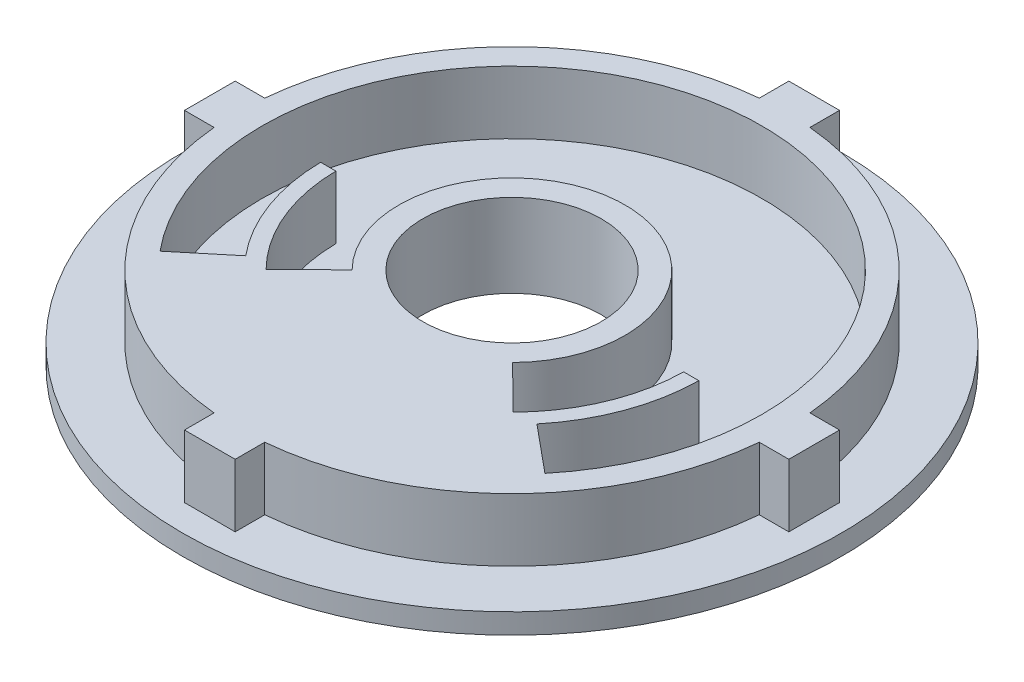
SolidWorks part; units mm, degrees
ref_plane "Front Plane" through (0, 0, 0) normal (0, 0, 1) x (1, 0, 0)
ref_plane "Top Plane" through (0, 0, 0) normal (0, 1, 0) x (1, 0, 0)
ref_plane "Right Plane" through (0, 0, 0) normal (1, 0, 0) x (0, 0, -1)
sketch "Sketch1" plane through (0, 0, 0) normal (0, 1, 0) x (1, 0, 0)
  line L0 (-17.5, -17.3601) -> (-13.2404, -13.1345)
  line L1 (0, -55) -> (0, 55) construction
  line L2 (17.5, -17.3601) -> (13.2404, -13.1345)
  line L3 (-18.6487, -0.2213) -> (-17.1486, -0.2214)
  line L4 (-17.5, -17.3601) -> (3.5272, -38.5567) construction
  line L5 (18.6487, -0.2213) -> (17.1486, -0.2214)
  line L6 (-12.1755, -12.0781) -> (-7.9158, -7.8525)
  line L7 (12.1755, -12.0781) -> (7.9158, -7.8525)
  circle A0 centre (0, 0) radius 27
  arc A1 (7.9158, -7.8525) -> (-7.9158, -7.8525) centre (0, 0) ccw
  arc A2 (17.5, -17.3601) -> (-17.5, -17.3601) centre (0, 0) ccw
  circle A3 centre (0, 0) radius 8.8
  arc A4 (14.1575, 11.0034) -> (12.7079, -12.6063) centre (-0.0251, 0.0249) cw construction
  circle A5 centre (0, 0) radius 17.9 construction
  arc A6 (-13.2404, -13.1345) -> (-18.6487, -0.2213) centre (0, 0) cw
  arc A7 (-12.1755, -12.0781) -> (-17.1486, -0.2214) centre (0, 0) cw
  arc A8 (13.2404, -13.1345) -> (18.6487, -0.2213) centre (0, 0) ccw
  arc A9 (12.1755, -12.0781) -> (17.1486, -0.2214) centre (0, 0) ccw
  dimension "D1" = 54
  dimension "D2" = 2.35
  dimension "D3" = 13.5
  dimension "D4" = 2.35
  dimension "D6" = 1.5
  dimension "D7" = 0.75
  dimension "D8" = 14
  dimension "D5" = 35
extrude "Boss-Extrude1" add sketch "Sketch1" along normal blind 6.2
sketch "Sketch2" plane through (0, 0, 0) normal (0, -1, 0) x (1, 0, 0)
  circle A0 centre (0, 0) radius 32.5
  circle A1 centre (0, 0) radius 8.8
  circle A2 centre (0, 0) radius 8.8 construction
  dimension "D1" = 65
extrude "Boss-Extrude2" add sketch "Sketch2" along normal blind 2
sketch "Sketch3" plane through (0, 0, 0) normal (0, 1, 0) x (1, 0, 0)
  line L0 (0, -55) -> (0, 55) construction
  line L1 (-2.5, 29.8) -> (2.5, 29.8)
  line L2 (-2.5, 29.8) -> (-2.5, 25.4032)
  line L3 (-2.5, 25.4032) -> (2.5, 25.4032)
  line L4 (2.5, 29.8) -> (2.5, 25.4032)
  line L5 (-2.5, 29.8) -> (2.5, 25.4032) construction
  line L6 (-2.5, 25.4032) -> (2.5, 29.8) construction
  line L7 (29.8, 2.5) -> (25.4032, 2.5)
  line L8 (29.8, 2.5) -> (29.8, -2.5)
  line L9 (29.8, -2.5) -> (25.4032, -2.5)
  line L10 (25.4032, 2.5) -> (25.4032, -2.5)
  line L11 (2.5, -29.8) -> (2.5, -25.4032)
  line L12 (2.5, -29.8) -> (-2.5, -29.8)
  line L13 (-2.5, -29.8) -> (-2.5, -25.4032)
  line L14 (2.5, -25.4032) -> (-2.5, -25.4032)
  line L15 (-29.8, -2.5) -> (-25.4032, -2.5)
  line L16 (-29.8, -2.5) -> (-29.8, 2.5)
  line L17 (-29.8, 2.5) -> (-25.4032, 2.5)
  line L18 (-25.4032, -2.5) -> (-25.4032, 2.5)
  circle A1 centre (0, 0) radius 27 construction
  point P0 (0, 27.6016)
  dimension "D2" = 29.8
  dimension "D1" = 5
  dimension "D3" = 4
extrude "Boss-Extrude3" add sketch "Sketch3" along normal up to surface (6.2 mm away) up to face at (0, 6.2, 3.562)
sketch "Sketch5" plane through (0, 0, 0) normal (0, 1, 0) x (1, 0, 0)
  line L0 (-18.9776, -15.7313) -> (-13.2035, -10.9449)
  line L2 (-12.1755, -12.0781) -> (-17.7339, -18.2046)
  line L3 (-17.7339, -18.2046) -> (-18.9776, -15.7313)
  line L8 (-18.9776, -15.7313) -> (-26.2675, -6.937) construction
  arc A0 (17.5, -17.3601) -> (-17.5, -17.3601) centre (0, 0) ccw construction
  arc A1 (17.5, -17.3601) -> (-17.5, -17.3601) centre (0, 0) ccw construction
  arc A2 (-12.1755, -12.0781) -> (-13.2035, -10.9449) centre (0, 0) cw
  arc A3 (-17.1486, -0.2214) -> (-12.1755, -12.0781) centre (0, 0) ccw construction
  point P1 (-18.9776, -15.7313)
  point P3 (-14.0059, -9.6394)
  point P5 (-12.0152, -11.9191)
  point P6 (0, 0)
  point P7 (0, 0)
  point P17 (-12.1755, -12.0781)
extrude "Boss-Extrude4" add sketch "Sketch5" along normal up to surface (6.2 mm away) up to face at (0, 6.2, 0)
mirror "Mirror2" about plane through (0, 0, 0) normal (1, 0, 0) of "Boss-Extrude4"
